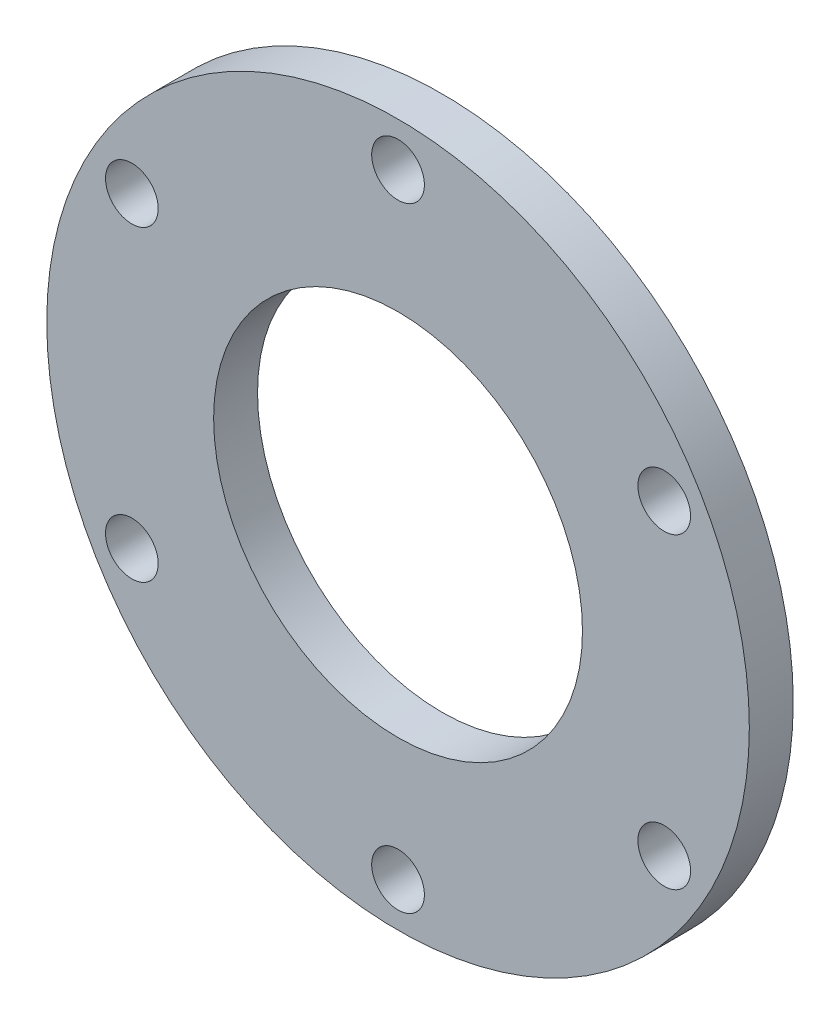
SolidWorks part; units mm, degrees
material "Plain Carbon Steel"
ref_plane "Front Plane" through (0, 0, 0) normal (0, 0, 1) x (1, 0, 0)
ref_plane "Top Plane" through (0, 0, 0) normal (0, 1, 0) x (1, 0, 0)
ref_plane "Right Plane" through (0, 0, 0) normal (1, 0, 0) x (0, 0, -1)
sketch "Base Sketch" plane through (0, 0, 0) normal (0, 0, 1) x (1, 0, 0)
  circle A0 centre (0, 0) radius 25.4
  circle A1 centre (0, 0) radius 13.335
  circle A2 centre (0, 0) radius 22.225 construction
  circle A3 centre (0, 22.225) radius 1.905
  circle A4 centre (19.2474, 11.1125) radius 1.905
  circle A5 centre (19.2474, -11.1125) radius 1.905
  circle A6 centre (0, -22.225) radius 1.905
  circle A7 centre (-19.2474, -11.1125) radius 1.905
  circle A8 centre (-19.2474, 11.1125) radius 1.905
  point P19 (0, 0)
  dimension "D1" = 50.8
  dimension "D2" = 26.67
  dimension "D3" = 44.45
  dimension "D4" = 3.81
  dimension "D5" = 6
extrude "Base Extrude" add sketch "Base Sketch" against normal blind 3.175
